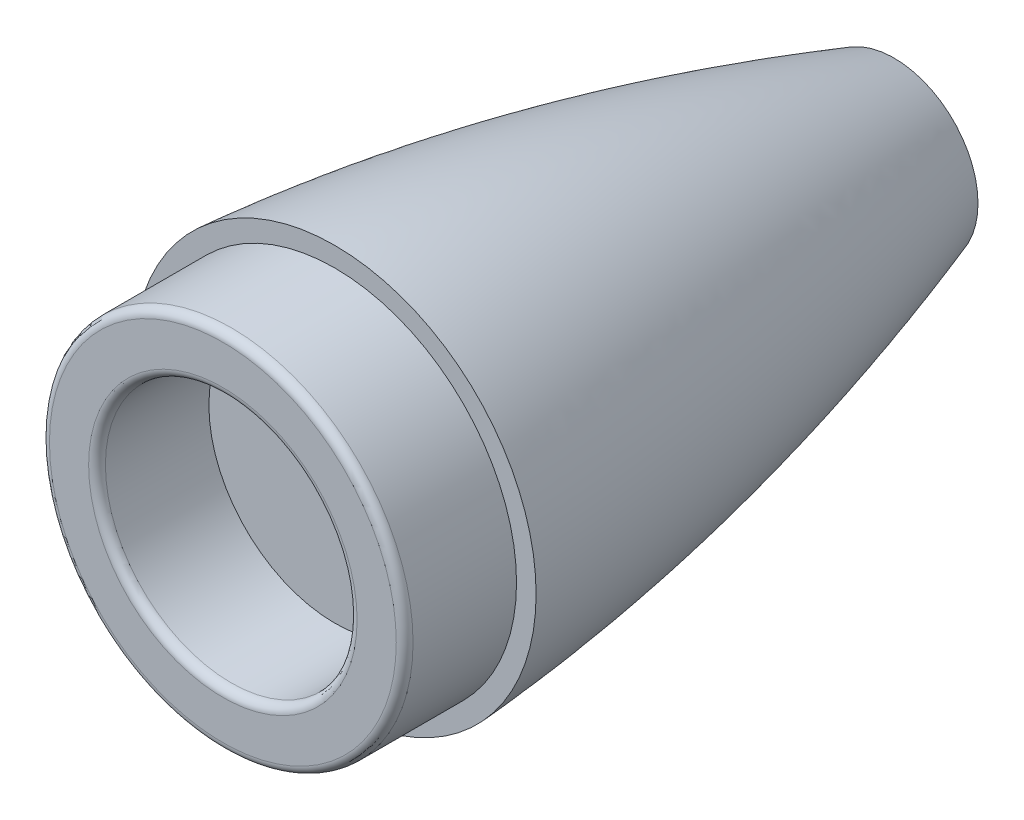
SolidWorks part; units mm, degrees
ref_plane "Front Plane" through (0, 0, 0) normal (0, 0, 1) x (1, 0, 0)
ref_plane "Top Plane" through (0, 0, 0) normal (0, 1, 0) x (1, 0, 0)
ref_plane "Right Plane" through (0, 0, 0) normal (1, 0, 0) x (0, 0, -1)
sketch "Sketch1" plane through (0, 0, 0) normal (0, 0, 1) x (1, 0, 0)
  circle A0 centre (0, 0) radius 45
  circle A1 centre (0, 0) radius 65
  dimension "D1" = 90
  dimension "D2" = 130
extrude "Boss-Extrude1" add sketch "Sketch1" against normal blind 40
fillet "Fillet1" radius 3 2 edges at (45, 0, 0) (65, 0, 0)
sketch "Sketch2" plane through (0, 0, 0) normal (1, 0, 0) x (0, 0, -1)
  line L0 (40, 0) -> (240, 0)
  line L1 (40, -65) -> (40, 65) construction
  line L2 (40, 0) -> (40, 72)
  line L3 (240, 0) -> (240, 30)
  spline S0 degree 2 poles (40, 72) (137.5973, 64.8545) (240, 30) knots 0 0 0 1 1 1
  dimension "D1" = 200
  dimension "D2" = 72
  dimension "D3" = 30
revolve "Revolve1" add sketch "Sketch2" angle 360 about L0
sketch "Sketch4" plane through (0, 0, -240) normal (0, 0, -1) x (-1, 0, 0)
  circle A0 centre (0, 0) radius 10
  dimension "D1" = 20
extrude "Cut-Extrude1" cut sketch "Sketch4" against normal blind 20
